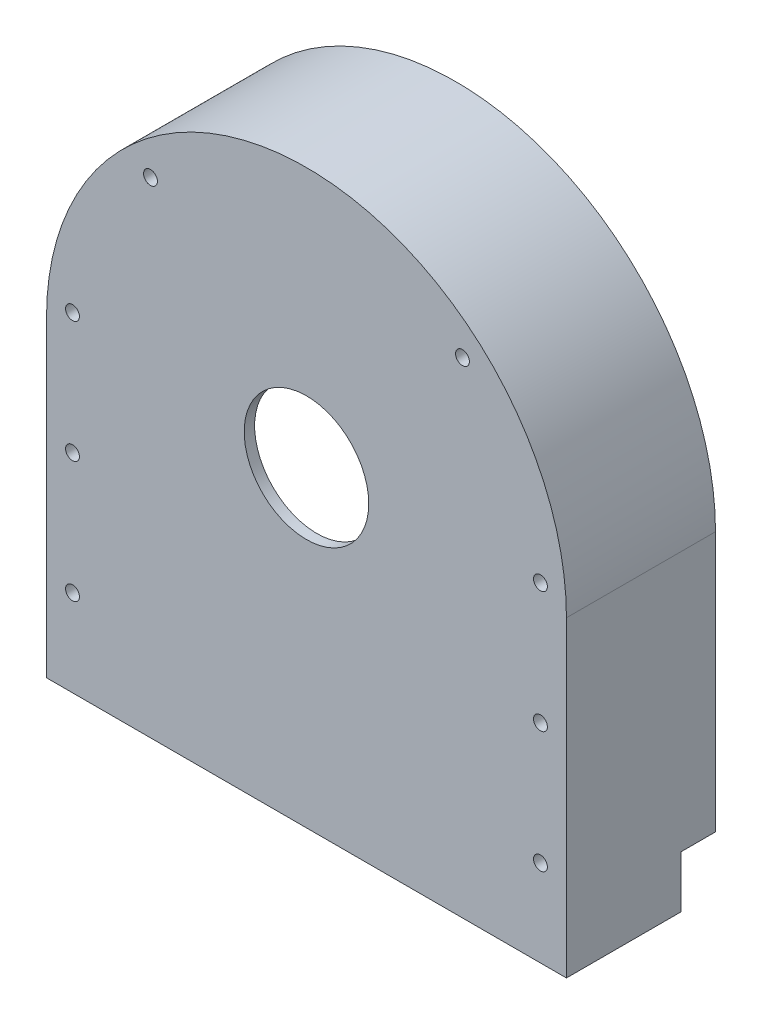
SolidWorks part; units mm, degrees
ref_plane "Front Plane" through (0, 0, 0) normal (0, 0, 1) x (1, 0, 0)
ref_plane "Top Plane" through (0, 0, 0) normal (0, 1, 0) x (1, 0, 0)
ref_plane "Right Plane" through (0, 0, 0) normal (1, 0, 0) x (0, 0, -1)
sketch "Sketch1" plane through (0, 0, 0) normal (0, 0, 1) x (1, 0, 0)
  line L1 (-75, 0) -> (-75, -75)
  line L2 (75, 0) -> (75, -75)
  line L5 (-75, -75) -> (-75, -90)
  line L6 (75, -75) -> (75, -90)
  line L7 (-75, -90) -> (75, -90)
  arc A0 (75, 0) -> (-75, 0) centre (0, 0) ccw
  circle A1 centre (0, 0) radius 17.96
  dimension "D1" = 75
  dimension "D2" = 150
  dimension "D3" = 15
extrude "Boss-Extrude1" add sketch "Sketch1" along normal blind 3
sketch "Sketch2" plane through (0, 0, 0) normal (0, 0, -1) x (-1, 0, 0)
  line L0 (-75, -90) -> (75, -90)
  line L1 (-75, -90) -> (-75, -75)
  line L2 (75, -90) -> (75, -75)
  line L3 (-75, -75) -> (75, -75)
  dimension "D1" = 15
extrude "Boss-Extrude2" add sketch "Sketch2" along normal blind 30
sketch "Sketch3" plane through (0, 0, 0) normal (0, 0, -1) x (-1, 0, 0)
  line L3 (75, 0) -> (75, -75)
  line L4 (-75, -75) -> (-75, 0)
  line L5 (72, 0) -> (72, -75)
  line L6 (-72, -75) -> (-72, 0)
  line L7 (72, 0) -> (72, -75)
  line L8 (-72, -75) -> (-72, 0)
  line L9 (-72, -75) -> (-75, -75)
  line L10 (75, -75) -> (72, -75)
  arc A3 (75, 0) -> (-75, 0) centre (0, 0) ccw
  arc A4 (72, 0) -> (-72, 0) centre (0, 0) ccw
  arc A5 (72, 0) -> (-72, 0) centre (0, 0) ccw
  dimension "D1" = 3
  dimension "D2" = 3
extrude "Boss-Extrude3" add sketch "Sketch3" along normal blind 40
fillet "Fillet1" radius 2 4 edges at (72, -37.5, 0) (0, 72, 0) (-72, -37.5, 0) (0, -75, 0)
sketch "Sketch4" plane through (0, 0, 3) normal (0, 0, 1) x (1, 0, 0)
  line L0 (-75, -90) -> (75, -90) construction
  line L1 (-75, 0) -> (-75, -90) construction
  circle A0 centre (-67.5, -65) radius 2
  circle A1 centre (67.5, -65) radius 2
  circle A2 centre (67.5, -30) radius 2
  circle A3 centre (67.5, 5) radius 2
  circle A4 centre (-67.5, -30) radius 2
  circle A5 centre (-67.5, 5) radius 2
  dimension "D1" = 25
  dimension "D2" = 7.5
  dimension "D3" = 2
  dimension "D4" = 3
extrude "Cut-Extrude1" cut sketch "Sketch4" against normal blind 4
sketch "Sketch5" plane through (0, 0, 3) normal (0, 0, 1) x (1, 0, 0)
  line L0 (-75, -90) -> (75, -90) construction
  line L1 (-75, 0) -> (-75, -90) construction
  circle A0 centre (-45, 50) radius 2
  circle A1 centre (45, 50) radius 2
  dimension "D1" = 140
  dimension "D2" = 30
  dimension "D3" = 2
sketch "Sketch6" plane through (0, 0, 0) normal (0, 0, -1) x (-1, 0, 0)
  line L0 (72, -75) -> (-72, -75) construction
  line L2 (-75, 0) -> (-75, -75) construction
  line L3 (72, -75) -> (-72, -75) construction
  circle A0 centre (43.16, -8.11) radius 2
  circle A1 centre (33.67, 17.57) radius 2
  circle A2 centre (33.67, 39.49) radius 2
  dimension "D1" = 66.89
  dimension "D3" = 108.67
  dimension "D5" = 114.49
  dimension "D2" = 118.16
  dimension "D4" = 92.57
  dimension "D6" = 108.67
extrude "Boss-Extrude4" add sketch "Sketch6" along normal blind 40
sketch "Sketch7" plane through (-75, 0, 0) normal (-1, 0, 0) x (0, 0, 1)
  line L0 (-40, -75) -> (-40, 0) construction
  line L1 (3, -90) -> (-30, -90) construction
  circle A0 centre (-23.57, 42.71) radius 4.76
  dimension "D1" = 16.43
  dimension "D3" = 9.52
  dimension "D2" = 132.71
extrude "Cut-Extrude4" cut sketch "Sketch7" against normal blind 30
extrude "Cut-Extrude6" cut sketch "Sketch5" against normal blind 60
